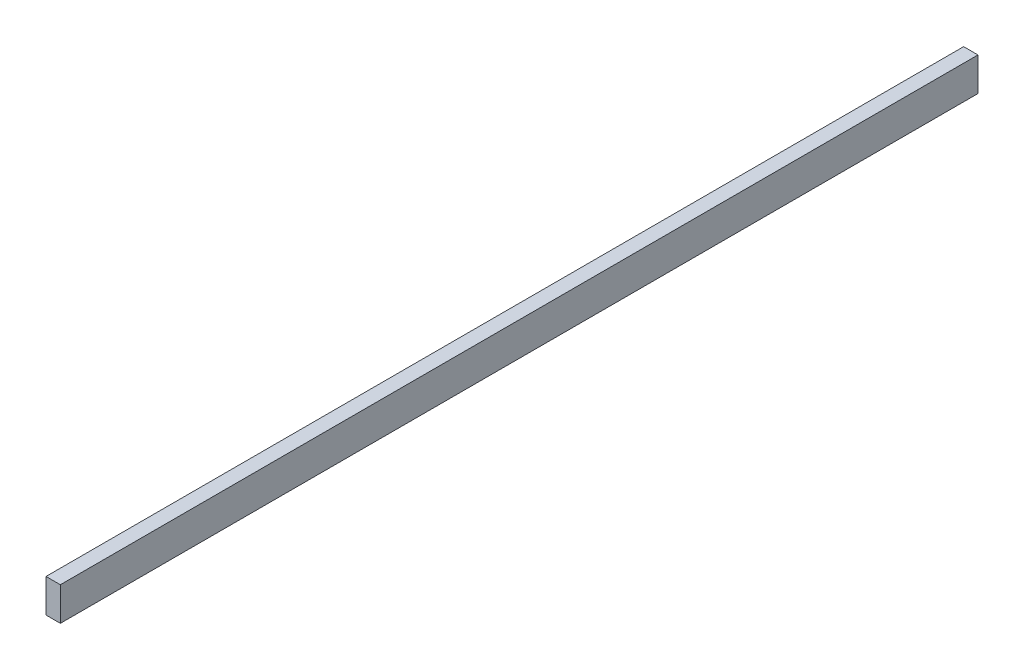
SolidWorks part; units mm, degrees
ref_plane "Front" through (0, 0, 0) normal (0, 0, 1) x (1, 0, 0)
ref_plane "Top" through (0, 0, 0) normal (0, 1, 0) x (1, 0, 0)
ref_plane "Right" through (0, 0, 0) normal (1, 0, 0) x (0, 0, -1)
sketch "Sketch1" plane through (0, 0, 0) normal (0, 0, 1) x (1, 0, 0)
  line L0 (-19.05, 44.45) -> (19.05, -44.45) construction
  line L1 (-19.05, 44.45) -> (19.05, 44.45)
  line L2 (-19.05, 44.45) -> (-19.05, -44.45)
  line L3 (-19.05, -44.45) -> (19.05, -44.45)
  line L4 (19.05, 44.45) -> (19.05, -44.45)
  dimension "D1" = 38.1
  dimension "D2" = 88.9
extrude "Extrude1" add sketch "Sketch1" along normal mid plane 2438.4
